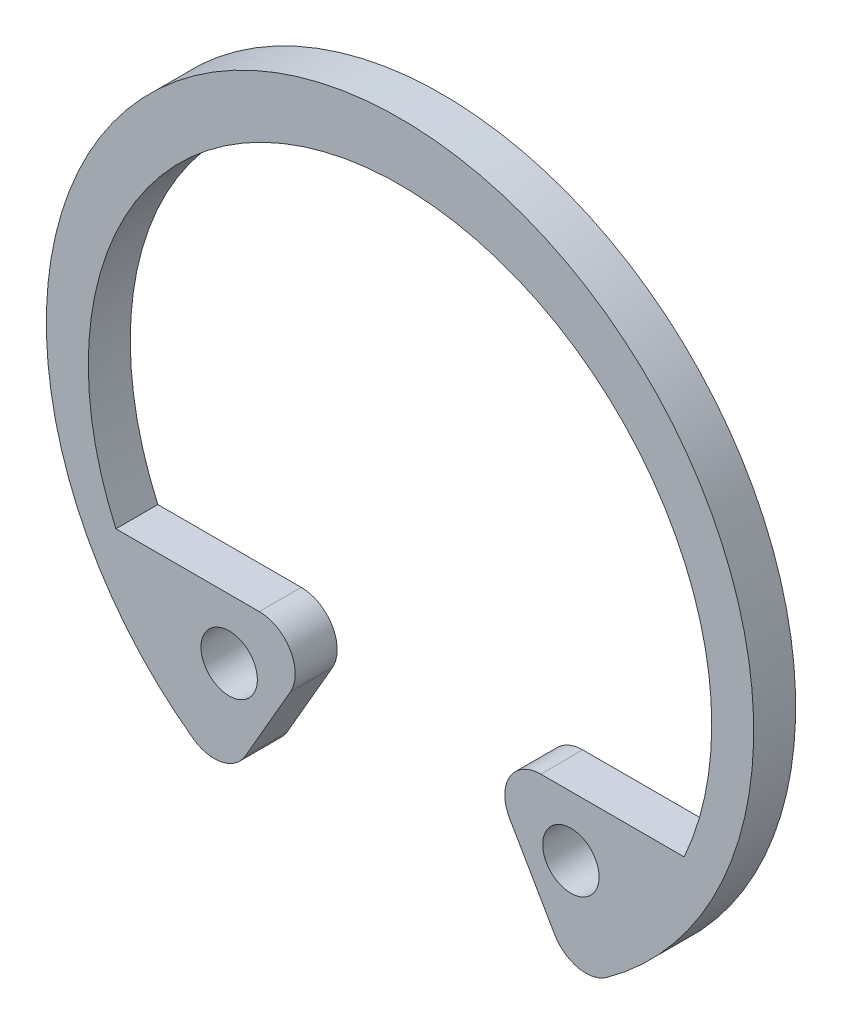
SolidWorks part; units mm, degrees
material "Alloy Steel"
ref_plane "Front Plane" through (0, 0, 0) normal (0, 0, 1) x (1, 0, 0)
ref_plane "Top Plane" through (0, 0, 0) normal (0, 1, 0) x (1, 0, 0)
ref_plane "Right Plane" through (0, 0, 0) normal (1, 0, 0) x (0, 0, -1)
sketch "Base Sketch" plane through (0, 0, 0) normal (0, 0, 1) x (1, 0, 0)
  line L0 (-2.3218, -4.191) -> (-3.275, -5.842)
  line L1 (0, 6.2738) -> (0, 0) construction
  line L4 (-6.0188, -3.048) -> (-2.9817, -3.048)
  line L5 (0, 0) -> (0, -3.048) construction
  line L6 (0, 0) -> (0, -4.318) construction
  line L7 (6.0188, -3.048) -> (2.9817, -3.048)
  line L8 (2.3218, -4.191) -> (3.275, -5.842)
  arc A0 (4.3804, -6.0792) -> (-4.3804, -6.0792) centre (0, 0) ccw
  arc A2 (6.0188, -3.048) -> (-6.0188, -3.048) centre (0, -0.3302) ccw
  arc A3 (3.275, -5.842) -> (4.3804, -6.0792) centre (3.935, -5.461) ccw
  arc A4 (2.9817, -3.048) -> (2.3218, -4.191) centre (2.9817, -3.81) ccw
  circle A5 centre (3.6195, -4.318) radius 0.5969
  circle A6 centre (-3.6195, -4.318) radius 0.5969
  arc A7 (-2.9817, -3.048) -> (-2.3218, -4.191) centre (-2.9817, -3.81) cw
  arc A8 (-3.275, -5.842) -> (-4.3804, -6.0792) centre (-3.935, -5.461) cw
  dimension "D1" = 14.986
  dimension "D2" = 10.5918
  dimension "D7" = 0.762
  dimension "D8" = 0.762
  dimension "D10" = 1.1938
  dimension "D3" = 0.3302
  dimension "D4" = 3.048
  dimension "D5" = 4.318
  dimension "D6" = 60
  dimension "D9" = 1.651
  dimension "D11" = 3.6195
  dimension "D12" = 4.318
  dimension "D13" = 6.0188
extrude "Base" add sketch "Base Sketch" against normal blind 0.889
